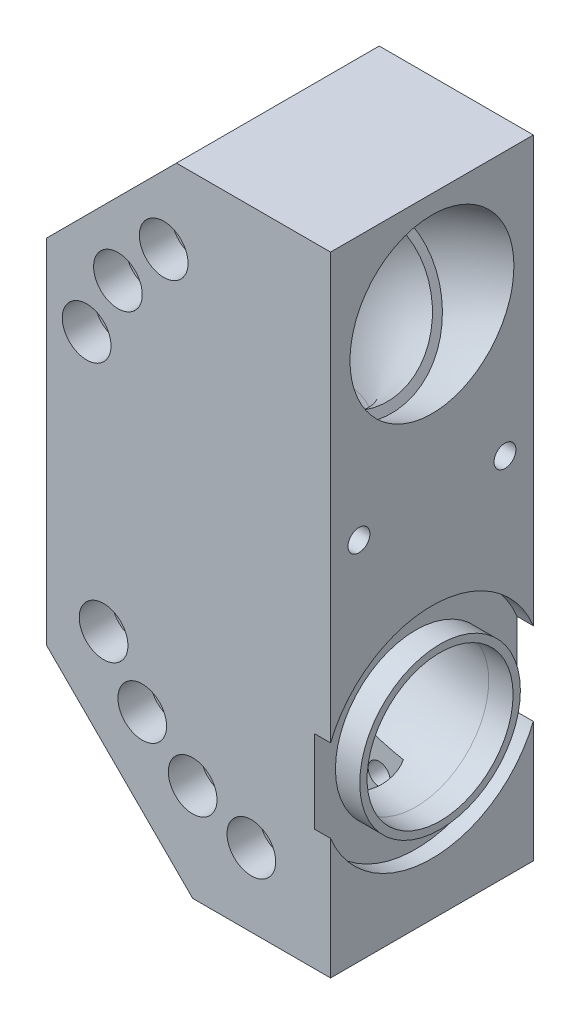
SolidWorks part; units mm, degrees
ref_plane "前视基准面" through (0, 0, 0) normal (0, 0, 1) x (1, 0, 0)
ref_plane "上视基准面" through (0, 0, 0) normal (0, 1, 0) x (1, 0, 0)
ref_plane "右视基准面" through (0, 0, 0) normal (1, 0, 0) x (0, 0, -1)
sketch "草图1" plane through (0, 0, 0) normal (0, 0, 1) x (1, 0, 0)
  line L0 (0, 0) -> (0, 39.5)
  line L1 (0, 39.5) -> (-19, 39.5)
  line L2 (-19, 39.5) -> (-35, 23.5)
  line L3 (-35, 23.5) -> (-35, -20)
  line L4 (-35, -20) -> (-17, -38)
  line L5 (-17, -38) -> (0, -38)
  line L6 (0, -38) -> (0, 0)
  line L7 (-20, 0) -> (-20, 5) construction
  line L8 (-2, -18) -> (0, -18) construction
  line L9 (-32, 0) -> (-32, 5) construction
  line L10 (-27.9808, -15) -> (-2, 0) construction
  line L11 (-2, 0) -> (-23.2132, -21.2132) construction
  line L12 (-17, -25.9808) -> (-2, 0) construction
  line L13 (-2, 0) -> (-9.7646, -28.9778) construction
  line L14 (-30.0702, 15.9446) -> (0, 5) construction
  line L15 (0, 5) -> (-32, 5) construction
  arc A0 (-2, -18) -> (-20, 0) centre (-2, 0) cw construction
  arc A1 (-20, 5) -> (-10, 22.3205) centre (0, 5) cw construction
  arc A2 (-10, 22.3205) -> (17.7264, 28.9448) centre (15, -20.9808) cw construction
  arc A3 (-2, -30) -> (-32, 0) centre (-2, 0) cw construction
  arc A4 (-32, 5) -> (-16, 32.7128) centre (0, 5) cw construction
  circle A5 centre (-27.9808, -15) radius 1.35
  arc A6 (-16, 32.7128) -> (18.3808, 40.927) centre (15, -20.9808) cw construction
  circle A7 centre (-23.2132, -21.2132) radius 1.35
  circle A8 centre (-17, -25.9808) radius 1.35
  circle A9 centre (-9.7646, -28.9778) radius 1.35
  circle A10 centre (-30.0702, 15.9446) radius 1.35
  circle A11 centre (-26.2129, 23.3544) radius 1.35
  circle A12 centre (-20.5692, 29.5134) radius 1.35
  dimension "D1" = 18
  dimension "D4" = 20
  dimension "D5" = 50
  dimension "D14" = 2.7
  dimension "D19" = 15
  dimension "D20" = 15
  dimension "D21" = 2.7
  dimension "D22" = 20
  dimension "D2" = 2
  dimension "D3" = 5
  dimension "D6" = 57.5
  dimension "D7" = 60
  dimension "D8" = 35
  dimension "D9" = 45
  dimension "D10" = 16
  dimension "D11" = 38
  dimension "D12" = 18
  dimension "D13" = 12
  dimension "D15" = 15
  dimension "D16" = 15
  dimension "D17" = 15
  dimension "D18" = 15
extrude "凸台-拉伸1" add sketch "草图1" along normal mid plane 25
sketch "草图2" plane through (0, 0, 0) normal (0, 0, 1) x (1, 0, 0)
  line L0 (-2, -18) -> (0, -18) construction
  line L2 (-20, 0) -> (-20, 5) construction
  line L3 (-2, -18) -> (0, -18)
  line L4 (-20, 0) -> (-20, 5)
  arc A0 (-20, 0) -> (-2, -18) centre (-2, 0) ccw construction
  arc A1 (-10, 22.3205) -> (-20, 5) centre (0, 5) ccw construction
  arc A2 (17.7264, 28.9448) -> (-10, 22.3205) centre (15, -20.9808) ccw construction
  arc A3 (-20, 0) -> (-2, -18) centre (-2, 0) ccw
  arc A4 (-10, 22.3205) -> (-20, 5) centre (0, 5) ccw
  arc A5 (17.7264, 28.9448) -> (-10, 22.3205) centre (15, -20.9808) ccw
sketch "草图3" plane through (0, 0, 0) normal (1, 0, 0) x (0, 0, -1)
  line L0 (0, 0) -> (0, -18) construction
  circle A0 centre (0, -18) radius 9
  dimension "D1" = 18
sweep "切除-扫描1" cut profiles "草图3" path "草图2"
sketch "草图4" plane through (0, 0, 0) normal (1, 0, 0) x (0, 0, -1)
  circle A0 centre (0, -18) radius 9.9
  circle A1 centre (0, -18) radius 9 construction
  circle A2 centre (0, -18) radius 9
  dimension "D1" = 19.8
extrude "凸台-拉伸2" add sketch "草图4" along normal blind 1
sketch "草图5" plane through (0, 0, 0) normal (1, 0, 0) x (0, 0, -1)
  circle A0 centre (0, -18) radius 13.5
  circle A1 centre (0, -18) radius 9.9 construction
  circle A2 centre (0, -18) radius 9.9
  dimension "D1" = 27
extrude "切除-拉伸1" cut sketch "草图5" against normal blind 2
ref_plane "基准面1" through (2.1651, 1.25, 0) normal (0.866, 0.5, 0) x (0, 0, -1)
sketch "草图6" plane through (2.1651, 1.25, 0) normal (0.866, 0.5, 0) x (0, 0, -1)
  circle A0 centre (0, 24.3301) radius 10.1
  circle A1 centre (0, 24.3301) radius 9 construction
  dimension "D1" = 20.2
sketch "草图7" plane through (0, 0, 0) normal (0, 0, 1) x (1, 0, 0)
  arc A0 (17.7264, 28.9448) -> (-10, 22.3205) centre (15, -20.9808) ccw construction
  arc A1 (17.7264, 28.9448) -> (-10, 22.3205) centre (15, -20.9808) ccw
sweep "切除-扫描4" cut profiles "草图6" path "草图7"
sketch "草图9" plane through (0, 0, 0) normal (0, 0, 1) x (1, 0, 0)
  arc A0 (-22.8121, 25.9035) -> (-23.9699, 26.9644) centre (-20.5692, 29.5134) ccw
  arc A1 (-23.9699, 26.9644) -> (-28.838, 20.0121) centre (-26.2129, 23.3544) ccw
  arc A2 (-28.838, 20.0121) -> (-27.445, 19.287) centre (-30.0702, 15.9446) ccw
  arc A3 (-24.2864, -17.1009) -> (-26.9076, -19.1123) centre (-27.9808, -15) ccw
  arc A4 (-26.9076, -19.1123) -> (-21.1123, -24.9076) centre (-23.2132, -21.2132) ccw
  arc A5 (-21.1123, -24.9076) -> (-14.0145, -29.0055) centre (-17, -25.9808) ccw
  arc A6 (-14.0145, -29.0055) -> (-12.7501, -25.953) centre (-9.7646, -28.9778) ccw
  circle A7 centre (-9.7646, -28.9778) radius 1.35 construction
  arc A8 (-27.445, 19.287) -> (-22.8121, 25.9035) centre (-26.2129, 23.3544) ccw
  arc A9 (-19.1009, -22.2864) -> (-24.2864, -17.1009) centre (-23.2132, -21.2132) ccw
  arc A10 (-12.7501, -25.953) -> (-19.1009, -22.2864) centre (-17, -25.9808) ccw
  point P19 (-26.9686, 18.403)
  dimension "D1" = 8.5
extrude "切除-拉伸2" cut sketch "草图9" against normal mid plane 6.5
sketch "草图10" plane through (0, 0, 0) normal (1, 0, 0) x (0, 0, -1)
  line L0 (0, 39.5) -> (0, -38) construction
  line L1 (-12.5, 39.5) -> (12.5, 39.5) construction
  line L2 (-12.5, -38) -> (12.5, -38) construction
  circle A0 centre (-9, 7) radius 1.35
  circle A1 centre (9, 7) radius 1.35
  circle A2 centre (0, -18) radius 9 construction
  dimension "D1" = 25
  dimension "D2" = 18
  dimension "D3" = 2.7
extrude "切除-拉伸3" cut sketch "草图10" against normal blind 8
sketch "草图11" plane through (0, 0, 12.5) normal (0, 0, 1) x (1, 0, 0)
  circle A0 centre (-20.5692, 29.5134) radius 1.6
  circle A1 centre (-26.2129, 23.3544) radius 1.6
  circle A2 centre (-30.0702, 15.9446) radius 1.6
  circle A3 centre (-27.9808, -15) radius 1.6
  circle A4 centre (-23.2132, -21.2132) radius 1.6
  circle A5 centre (-17, -25.9808) radius 1.6
  circle A6 centre (-9.7646, -28.9778) radius 1.6
  dimension "D1" = 3.2
extrude "切除-拉伸4" cut sketch "草图11" against normal up to next
sketch "草图12" plane through (0, 0, 12.5) normal (0, 0, 1) x (1, 0, 0)
  circle A0 centre (-20.5692, 29.5134) radius 3
  circle A1 centre (-26.2129, 23.3544) radius 3
  circle A2 centre (-30.0702, 15.9446) radius 3
  circle A3 centre (-27.9808, -15) radius 3
  circle A4 centre (-23.2132, -21.2132) radius 3
  circle A5 centre (-17, -25.9808) radius 3
  circle A6 centre (-9.7646, -28.9778) radius 3
  circle A7 centre (-17, -25.9808) radius 1.6 construction
  point P20 (0, 0)
  dimension "D1" = 6
extrude "切除-拉伸5" cut sketch "草图12" against normal blind 4
